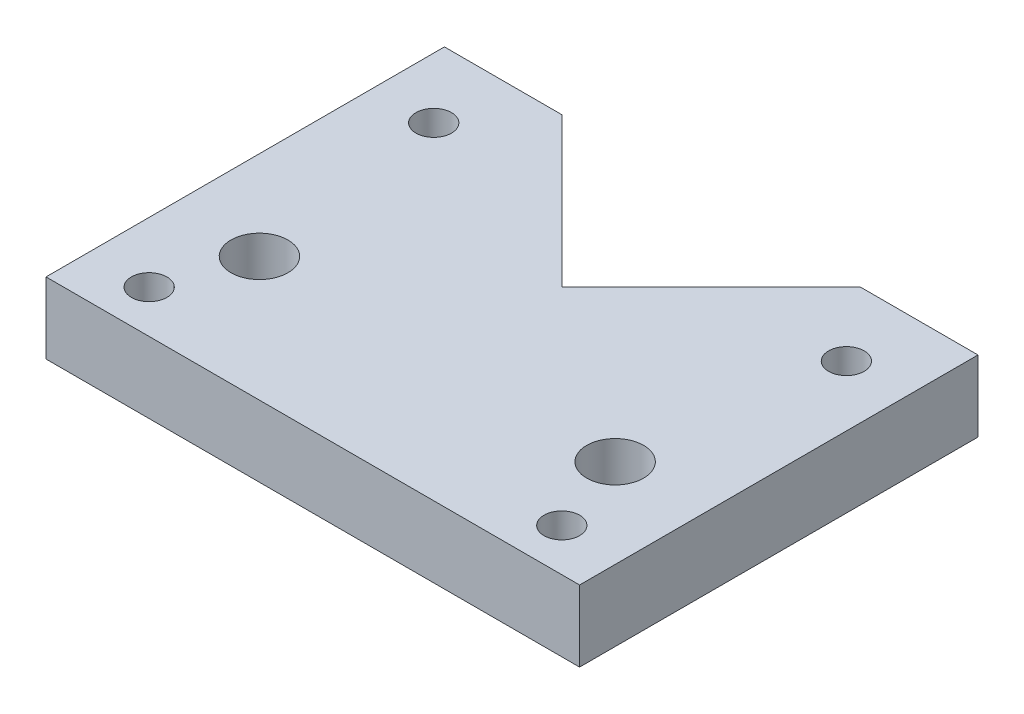
SolidWorks part; units mm, degrees
ref_plane "Front Plane" through (0, 0, 0) normal (0, 0, 1) x (1, 0, 0)
ref_plane "Top Plane" through (0, 0, 0) normal (0, 1, 0) x (1, 0, 0)
ref_plane "Right Plane" through (0, 0, 0) normal (1, 0, 0) x (0, 0, -1)
sketch "Sketch1" plane through (0, 0, 0) normal (0, 0, 1) x (1, 0, 0)
  line L0 (-37.5, 0) -> (37.5, 0)
  line L1 (-37.5, 0) -> (-37.5, -10)
  line L2 (-37.5, -10) -> (37.5, -10)
  line L3 (37.5, -10) -> (37.5, 0)
  line L4 (0, 0) -> (0, -10) construction
  dimension "D1" = 10
  dimension "D2" = 75
extrude "Boss-Extrude1" add sketch "Sketch1" along normal blind 35
sketch "Sketch2" plane through (0, 0, 0) normal (0, 1, 0) x (1, 0, 0)
  line L0 (-37.5, -17.5) -> (37.5, -17.5) construction
  line L1 (-37.5, -35) -> (-37.5, 0) construction
  line L2 (37.5, -35) -> (37.5, 0) construction
  line L3 (0, 0) -> (0, -35) construction
  line L4 (37.5, 0) -> (-37.5, 0) construction
  line L5 (37.5, -35) -> (-37.5, -35) construction
  circle A0 centre (-25, -17.5) radius 4
  circle A1 centre (25, -17.5) radius 4
  dimension "D1" = 50
  dimension "D2" = 8
extrude "Cut-Extrude1" cut sketch "Sketch2" against normal through all both and the other way through all
sketch "Sketch3" plane through (0, 0, 0) normal (0, 1, 0) x (1, 0, 0)
  line L0 (-37.5, -29) -> (37.5, -29) construction
  line L1 (-37.5, -35) -> (-37.5, 0) construction
  line L2 (37.5, -35) -> (37.5, 0) construction
  line L3 (37.5, -35) -> (-37.5, -35) construction
  line L4 (0, -35) -> (0, 0) construction
  circle A0 centre (-29, -29) radius 2.5
  circle A1 centre (29, -29) radius 2.5
  dimension "D2" = 5
  dimension "D3" = 58
  dimension "D1" = 6
extrude "Cut-Extrude2" cut sketch "Sketch3" against normal through all both and the other way through all
sketch "Sketch4" plane through (0, 0, 0) normal (0, 0, -1) x (-1, 0, 0)
  line L1 (37.5, -10) -> (-37.5, -10)
  line L2 (37.5, -10) -> (37.5, 0)
  line L3 (37.5, 0) -> (-37.5, 0)
  line L4 (-37.5, -10) -> (-37.5, 0)
extrude "Boss-Extrude2" add sketch "Sketch4" along normal blind 21
sketch "Sketch5" plane through (0, 0, 0) normal (0, 1, 0) x (1, 0, 0)
  line L0 (-37.5, 11) -> (37.5, 11) construction
  line L1 (-37.5, -35) -> (-37.5, 21) construction
  line L2 (37.5, -35) -> (37.5, 21) construction
  line L3 (0, 21) -> (0, -35) construction
  line L4 (-37.5, 21) -> (37.5, 21) construction
  line L5 (37.5, -35) -> (-37.5, -35) construction
  circle A0 centre (-29, 11) radius 2.5
  circle A1 centre (29, 11) radius 2.5
  dimension "D1" = 5
  dimension "D2" = 58
  dimension "D3" = 10
extrude "Cut-Extrude3" cut sketch "Sketch5" against normal through all both and the other way through all
sketch "Sketch6" plane through (0, -10, 0) normal (0, -1, 0) x (1, 0, 0)
  line L1 (-24.3812, 29) -> (-26.6906, 33)
  line L2 (-26.6906, 33) -> (-31.3094, 33)
  line L3 (-31.3094, 33) -> (-33.6188, 29)
  line L4 (-33.6188, 29) -> (-31.3094, 25)
  line L5 (-31.3094, 25) -> (-26.6906, 25)
  line L6 (-26.6906, 25) -> (-24.3812, 29)
  line L7 (33.6188, 29) -> (31.3094, 33)
  line L8 (31.3094, 33) -> (26.6906, 33)
  line L9 (26.6906, 33) -> (24.3812, 29)
  line L10 (24.3812, 29) -> (26.6906, 25)
  line L11 (26.6906, 25) -> (31.3094, 25)
  line L12 (31.3094, 25) -> (33.6188, 29)
  line L13 (-24.3812, -11) -> (-26.6906, -7)
  line L14 (-26.6906, -7) -> (-31.3094, -7)
  line L15 (-31.3094, -7) -> (-33.6188, -11)
  line L16 (-33.6188, -11) -> (-31.3094, -15)
  line L17 (-31.3094, -15) -> (-26.6906, -15)
  line L18 (-26.6906, -15) -> (-24.3812, -11)
  line L19 (33.6188, -11) -> (31.3094, -7)
  line L20 (31.3094, -7) -> (26.6906, -7)
  line L21 (26.6906, -7) -> (24.3812, -11)
  line L22 (24.3812, -11) -> (26.6906, -15)
  line L23 (26.6906, -15) -> (31.3094, -15)
  line L24 (31.3094, -15) -> (33.6188, -11)
  circle A0 centre (-29, 29) radius 4 construction
  circle A1 centre (29, 29) radius 4 construction
  circle A2 centre (-29, -11) radius 4 construction
  circle A3 centre (29, -11) radius 4 construction
  point P28 (-29, 25)
  dimension "D1" = 8
  dimension "D2" = 8
  dimension "D3" = 8
  dimension "D4" = 8
extrude "Cut-Extrude4" cut sketch "Sketch6" against normal blind 4
sketch "Sketch7" plane through (0, 0, 0) normal (0, 1, 0) x (1, 0, 0)
  line L0 (0, 0) -> (21, 21)
  line L1 (-37.5, 21) -> (37.5, 21) construction
  line L2 (0, 0) -> (0, 21) construction
  line L3 (0, 0) -> (-21, 21)
  line L4 (21, 21) -> (-21, 21)
  dimension "D1" = 42
extrude "Cut-Extrude5" cut sketch "Sketch7" against normal through all both and the other way through all
